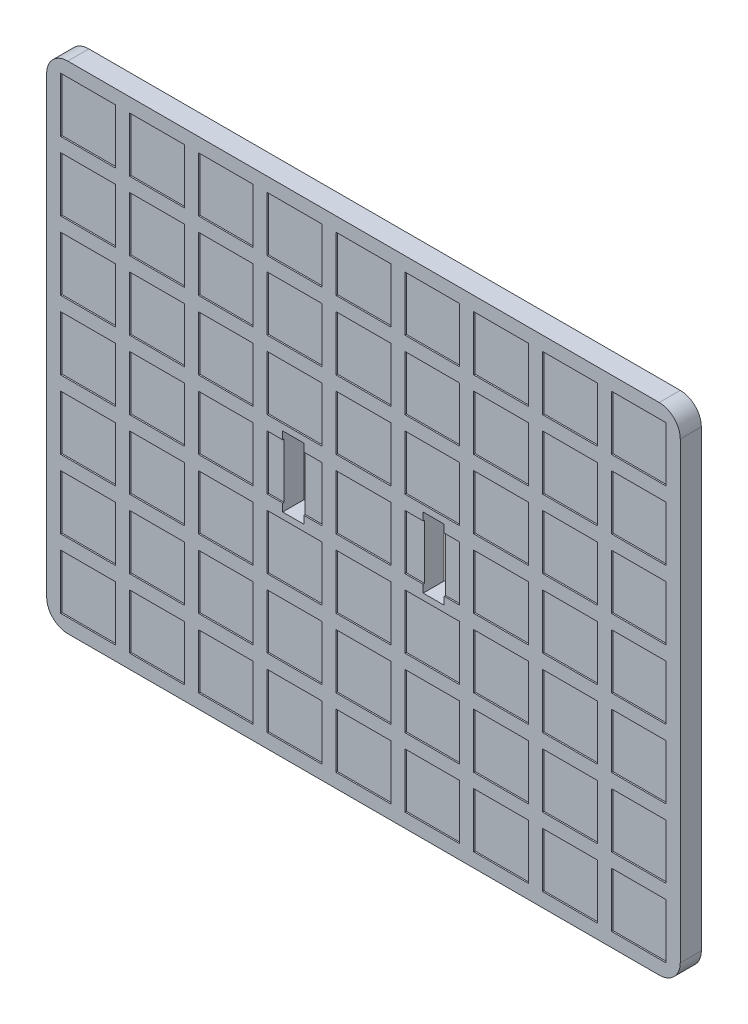
SolidWorks part; units mm, degrees
material "Maple"
ref_plane "Front Plane" through (0, 0, 0) normal (0, 0, 1) x (1, 0, 0)
ref_plane "Top Plane" through (0, 0, 0) normal (0, 1, 0) x (1, 0, 0)
ref_plane "Right Plane" through (0, 0, 0) normal (1, 0, 0) x (0, 0, -1)
sketch "Sketch1" plane through (0, 0, 0) normal (0, 0, 1) x (1, 0, 0)
  line L0 (-10, 0) -> (0, 0) construction
  line L1 (42.1, 35.3) -> (-42.1, 35.3)
  line L2 (45.1, 32.3) -> (45.1, -32.3)
  line L3 (42.1, -35.3) -> (-42.1, -35.3)
  line L4 (-45.1, 32.3) -> (-45.1, -32.3)
  line L5 (45.1, 35.3) -> (-45.1, -35.3) construction
  line L6 (45.1, -35.3) -> (-45.1, 35.3) construction
  line L7 (-11.5, 5) -> (-8.5, 5)
  line L8 (-11.5, 5) -> (-11.5, -5)
  line L9 (-11.5, -5) -> (-8.5, -5)
  line L10 (-8.5, 5) -> (-8.5, -5)
  line L11 (-11.5, 5) -> (-8.5, -5) construction
  line L12 (-11.5, -5) -> (-8.5, 5) construction
  line L13 (8.5, 5) -> (11.5, 5)
  line L14 (8.5, 5) -> (8.5, -5)
  line L15 (8.5, -5) -> (11.5, -5)
  line L16 (11.5, 5) -> (11.5, -5)
  line L17 (8.5, 5) -> (11.5, -5) construction
  line L18 (8.5, -5) -> (11.5, 5) construction
  line L19 (0, 0) -> (10, 0) construction
  arc A0 (-45.1, -32.3) -> (-42.1, -35.3) centre (-42.1, -32.3) ccw
  arc A1 (42.1, -35.3) -> (45.1, -32.3) centre (42.1, -32.3) ccw
  arc A2 (45.1, 32.3) -> (42.1, 35.3) centre (42.1, 32.3) ccw
  arc A3 (-42.1, 35.3) -> (-45.1, 32.3) centre (-42.1, 32.3) ccw
  point P0 (0, 0)
  point P5 (-10, 0)
  point P11 (10, 0)
  dimension "D6" = 3
  dimension "D1" = 20
  dimension "D2" = 3
  dimension "D3" = 10
  dimension "D4" = 90.2
  dimension "D5" = 70.6
extrude "Boss-Extrude1" add sketch "Sketch1" along normal blind 3
sketch "Sketch2" plane through (0, 0, 3) normal (0, 0, 1) x (1, 0, 0)
  line L1 (-43.1, 23.5) -> (-35.3, 23.5)
  line L2 (-43.1, 33.3) -> (-35.3, 33.3)
  line L3 (-43.1, 33.3) -> (-43.1, 25.5)
  line L4 (-43.1, 23.5) -> (-43.1, 15.7)
  line L5 (-43.1, 25.5) -> (-35.3, 25.5)
  line L6 (-35.3, 33.3) -> (-35.3, 25.5)
  line L7 (-33.3, 33.3) -> (-25.5, 33.3)
  line L8 (-33.3, 33.3) -> (-33.3, 25.5)
  line L9 (-33.3, 25.5) -> (-25.5, 25.5)
  line L10 (-25.5, 33.3) -> (-25.5, 25.5)
  line L11 (-35.3, 33.3) -> (-33.3, 33.3) construction
  line L12 (-23.5, 33.3) -> (-15.7, 33.3)
  line L13 (-23.5, 33.3) -> (-23.5, 25.5)
  line L14 (-23.5, 25.5) -> (-15.7, 25.5)
  line L15 (-15.7, 33.3) -> (-15.7, 25.5)
  line L16 (-13.7, 33.3) -> (-5.9, 33.3)
  line L17 (-13.7, 33.3) -> (-13.7, 25.5)
  line L18 (-13.7, 25.5) -> (-5.9, 25.5)
  line L19 (-5.9, 33.3) -> (-5.9, 25.5)
  line L20 (-3.9, 33.3) -> (3.9, 33.3)
  line L21 (-3.9, 33.3) -> (-3.9, 25.5)
  line L22 (-3.9, 25.5) -> (3.9, 25.5)
  line L23 (3.9, 33.3) -> (3.9, 25.5)
  line L24 (5.9, 33.3) -> (13.7, 33.3)
  line L25 (5.9, 33.3) -> (5.9, 25.5)
  line L26 (5.9, 25.5) -> (13.7, 25.5)
  line L27 (13.7, 33.3) -> (13.7, 25.5)
  line L28 (15.7, 33.3) -> (23.5, 33.3)
  line L29 (15.7, 33.3) -> (15.7, 25.5)
  line L30 (15.7, 25.5) -> (23.5, 25.5)
  line L31 (23.5, 33.3) -> (23.5, 25.5)
  line L32 (-43.1, 15.7) -> (-35.3, 15.7)
  line L33 (25.5, 33.3) -> (33.3, 33.3)
  line L34 (25.5, 33.3) -> (25.5, 25.5)
  line L35 (25.5, 25.5) -> (33.3, 25.5)
  line L36 (33.3, 33.3) -> (33.3, 25.5)
  line L37 (35.3, 33.3) -> (43.1, 33.3)
  line L38 (35.3, 33.3) -> (35.3, 25.5)
  line L39 (35.3, 25.5) -> (43.1, 25.5)
  line L40 (43.1, 33.3) -> (43.1, 25.5)
  line L41 (-23.5, 33.3) -> (-25.5, 33.3) construction
  line L42 (-13.7, 33.3) -> (-15.7, 33.3) construction
  line L43 (-3.9, 33.3) -> (-5.9, 33.3) construction
  line L44 (5.9, 33.3) -> (3.9, 33.3) construction
  line L45 (15.7, 33.3) -> (13.7, 33.3) construction
  line L46 (25.5, 33.3) -> (23.5, 33.3) construction
  line L47 (35.3, 33.3) -> (33.3, 33.3) construction
  line L48 (-35.3, 23.5) -> (-35.3, 15.7)
  line L49 (-33.3, 23.5) -> (-25.5, 23.5)
  line L50 (-33.3, 23.5) -> (-33.3, 15.7)
  line L51 (-33.3, 15.7) -> (-25.5, 15.7)
  line L52 (-25.5, 23.5) -> (-25.5, 15.7)
  line L53 (-35.3, 23.5) -> (-33.3, 23.5) construction
  line L54 (-23.5, 23.5) -> (-15.7, 23.5)
  line L55 (-23.5, 23.5) -> (-23.5, 15.7)
  line L56 (-23.5, 15.7) -> (-15.7, 15.7)
  line L57 (-15.7, 23.5) -> (-15.7, 15.7)
  line L58 (-13.7, 23.5) -> (-5.9, 23.5)
  line L59 (-13.7, 23.5) -> (-13.7, 15.7)
  line L60 (-13.7, 15.7) -> (-5.9, 15.7)
  line L61 (-5.9, 23.5) -> (-5.9, 15.7)
  line L62 (-3.9, 23.5) -> (3.9, 23.5)
  line L63 (-3.9, 23.5) -> (-3.9, 15.7)
  line L64 (-3.9, 15.7) -> (3.9, 15.7)
  line L65 (3.9, 23.5) -> (3.9, 15.7)
  line L66 (5.9, 23.5) -> (13.7, 23.5)
  line L67 (5.9, 23.5) -> (5.9, 15.7)
  line L68 (5.9, 15.7) -> (13.7, 15.7)
  line L69 (13.7, 23.5) -> (13.7, 15.7)
  line L70 (15.7, 23.5) -> (23.5, 23.5)
  line L71 (15.7, 23.5) -> (15.7, 15.7)
  line L72 (15.7, 15.7) -> (23.5, 15.7)
  line L73 (23.5, 23.5) -> (23.5, 15.7)
  line L74 (25.5, 23.5) -> (33.3, 23.5)
  line L75 (25.5, 23.5) -> (25.5, 15.7)
  line L76 (25.5, 15.7) -> (33.3, 15.7)
  line L77 (33.3, 23.5) -> (33.3, 15.7)
  line L78 (35.3, 23.5) -> (43.1, 23.5)
  line L79 (35.3, 23.5) -> (35.3, 15.7)
  line L80 (35.3, 15.7) -> (43.1, 15.7)
  line L81 (43.1, 23.5) -> (43.1, 15.7)
  line L82 (-23.5, 23.5) -> (-25.5, 23.5) construction
  line L83 (-13.7, 23.5) -> (-15.7, 23.5) construction
  line L84 (-3.9, 23.5) -> (-5.9, 23.5) construction
  line L85 (5.9, 23.5) -> (3.9, 23.5) construction
  line L86 (15.7, 23.5) -> (13.7, 23.5) construction
  line L87 (25.5, 23.5) -> (23.5, 23.5) construction
  line L88 (35.3, 23.5) -> (33.3, 23.5) construction
  line L90 (-43.1, 3.9) -> (-35.3, 3.9)
  line L91 (-43.1, 13.7) -> (-35.3, 13.7)
  line L92 (-43.1, 13.7) -> (-43.1, 5.9)
  line L93 (-43.1, 3.9) -> (-43.1, -3.9)
  line L94 (-43.1, 5.9) -> (-35.3, 5.9)
  line L95 (-35.3, 13.7) -> (-35.3, 5.9)
  line L96 (-33.3, 13.7) -> (-25.5, 13.7)
  line L97 (-33.3, 13.7) -> (-33.3, 5.9)
  line L98 (-33.3, 5.9) -> (-25.5, 5.9)
  line L99 (-25.5, 13.7) -> (-25.5, 5.9)
  line L100 (-35.3, 13.7) -> (-33.3, 13.7) construction
  line L101 (-23.5, 13.7) -> (-15.7, 13.7)
  line L102 (-23.5, 13.7) -> (-23.5, 5.9)
  line L103 (-23.5, 5.9) -> (-15.7, 5.9)
  line L104 (-15.7, 13.7) -> (-15.7, 5.9)
  line L105 (-13.7, 13.7) -> (-5.9, 13.7)
  line L106 (-13.7, 13.7) -> (-13.7, 5.9)
  line L107 (-13.7, 5.9) -> (-5.9, 5.9)
  line L108 (-5.9, 13.7) -> (-5.9, 5.9)
  line L109 (-3.9, 13.7) -> (3.9, 13.7)
  line L110 (-3.9, 13.7) -> (-3.9, 5.9)
  line L111 (-3.9, 5.9) -> (3.9, 5.9)
  line L112 (3.9, 13.7) -> (3.9, 5.9)
  line L113 (5.9, 13.7) -> (13.7, 13.7)
  line L114 (5.9, 13.7) -> (5.9, 5.9)
  line L115 (5.9, 5.9) -> (13.7, 5.9)
  line L116 (13.7, 13.7) -> (13.7, 5.9)
  line L117 (15.7, 13.7) -> (23.5, 13.7)
  line L118 (15.7, 13.7) -> (15.7, 5.9)
  line L119 (15.7, 5.9) -> (23.5, 5.9)
  line L120 (23.5, 13.7) -> (23.5, 5.9)
  line L121 (-43.1, -3.9) -> (-35.3, -3.9)
  line L122 (25.5, 13.7) -> (33.3, 13.7)
  line L123 (25.5, 13.7) -> (25.5, 5.9)
  line L124 (25.5, 5.9) -> (33.3, 5.9)
  line L125 (33.3, 13.7) -> (33.3, 5.9)
  line L126 (35.3, 13.7) -> (43.1, 13.7)
  line L127 (35.3, 13.7) -> (35.3, 5.9)
  line L128 (35.3, 5.9) -> (43.1, 5.9)
  line L129 (43.1, 13.7) -> (43.1, 5.9)
  line L130 (-23.5, 13.7) -> (-25.5, 13.7) construction
  line L131 (-13.7, 13.7) -> (-15.7, 13.7) construction
  line L132 (-3.9, 13.7) -> (-5.9, 13.7) construction
  line L133 (5.9, 13.7) -> (3.9, 13.7) construction
  line L134 (15.7, 13.7) -> (13.7, 13.7) construction
  line L135 (25.5, 13.7) -> (23.5, 13.7) construction
  line L136 (35.3, 13.7) -> (33.3, 13.7) construction
  line L137 (-35.3, 3.9) -> (-35.3, -3.9)
  line L138 (-33.3, 3.9) -> (-25.5, 3.9)
  line L139 (-33.3, 3.9) -> (-33.3, -3.9)
  line L140 (-33.3, -3.9) -> (-25.5, -3.9)
  line L141 (-25.5, 3.9) -> (-25.5, -3.9)
  line L142 (-35.3, 3.9) -> (-33.3, 3.9) construction
  line L143 (-23.5, 3.9) -> (-15.7, 3.9)
  line L144 (-23.5, 3.9) -> (-23.5, -3.9)
  line L145 (-23.5, -3.9) -> (-15.7, -3.9)
  line L146 (-15.7, 3.9) -> (-15.7, -3.9)
  line L147 (-13.7, 3.9) -> (-5.9, 3.9)
  line L148 (-13.7, 3.9) -> (-13.7, -3.9)
  line L149 (-13.7, -3.9) -> (-5.9, -3.9)
  line L150 (-5.9, 3.9) -> (-5.9, -3.9)
  line L151 (-3.9, 3.9) -> (3.9, 3.9)
  line L152 (-3.9, 3.9) -> (-3.9, -3.9)
  line L153 (-3.9, -3.9) -> (3.9, -3.9)
  line L154 (3.9, 3.9) -> (3.9, -3.9)
  line L155 (5.9, 3.9) -> (13.7, 3.9)
  line L156 (5.9, 3.9) -> (5.9, -3.9)
  line L157 (5.9, -3.9) -> (13.7, -3.9)
  line L158 (13.7, 3.9) -> (13.7, -3.9)
  line L159 (15.7, 3.9) -> (23.5, 3.9)
  line L160 (15.7, 3.9) -> (15.7, -3.9)
  line L161 (15.7, -3.9) -> (23.5, -3.9)
  line L162 (23.5, 3.9) -> (23.5, -3.9)
  line L163 (25.5, 3.9) -> (33.3, 3.9)
  line L164 (25.5, 3.9) -> (25.5, -3.9)
  line L165 (25.5, -3.9) -> (33.3, -3.9)
  line L166 (33.3, 3.9) -> (33.3, -3.9)
  line L167 (35.3, 3.9) -> (43.1, 3.9)
  line L168 (35.3, 3.9) -> (35.3, -3.9)
  line L169 (35.3, -3.9) -> (43.1, -3.9)
  line L170 (43.1, 3.9) -> (43.1, -3.9)
  line L171 (-23.5, 3.9) -> (-25.5, 3.9) construction
  line L172 (-13.7, 3.9) -> (-15.7, 3.9) construction
  line L173 (-3.9, 3.9) -> (-5.9, 3.9) construction
  line L174 (5.9, 3.9) -> (3.9, 3.9) construction
  line L175 (15.7, 3.9) -> (13.7, 3.9) construction
  line L176 (25.5, 3.9) -> (23.5, 3.9) construction
  line L177 (35.3, 3.9) -> (33.3, 3.9) construction
  line L178 (-43.1, -15.7) -> (-35.3, -15.7)
  line L179 (-43.1, -5.9) -> (-35.3, -5.9)
  line L180 (-43.1, -5.9) -> (-43.1, -13.7)
  line L181 (-43.1, -15.7) -> (-43.1, -23.5)
  line L182 (-43.1, -13.7) -> (-35.3, -13.7)
  line L183 (-35.3, -5.9) -> (-35.3, -13.7)
  line L184 (-33.3, -5.9) -> (-25.5, -5.9)
  line L185 (-33.3, -5.9) -> (-33.3, -13.7)
  line L186 (-33.3, -13.7) -> (-25.5, -13.7)
  line L187 (-25.5, -5.9) -> (-25.5, -13.7)
  line L188 (-35.3, -5.9) -> (-33.3, -5.9) construction
  line L189 (-23.5, -5.9) -> (-15.7, -5.9)
  line L190 (-23.5, -5.9) -> (-23.5, -13.7)
  line L191 (-23.5, -13.7) -> (-15.7, -13.7)
  line L192 (-15.7, -5.9) -> (-15.7, -13.7)
  line L193 (-13.7, -5.9) -> (-5.9, -5.9)
  line L194 (-13.7, -5.9) -> (-13.7, -13.7)
  line L195 (-13.7, -13.7) -> (-5.9, -13.7)
  line L196 (-5.9, -5.9) -> (-5.9, -13.7)
  line L197 (-3.9, -5.9) -> (3.9, -5.9)
  line L198 (-3.9, -5.9) -> (-3.9, -13.7)
  line L199 (-3.9, -13.7) -> (3.9, -13.7)
  line L200 (3.9, -5.9) -> (3.9, -13.7)
  line L201 (5.9, -5.9) -> (13.7, -5.9)
  line L202 (5.9, -5.9) -> (5.9, -13.7)
  line L203 (5.9, -13.7) -> (13.7, -13.7)
  line L204 (13.7, -5.9) -> (13.7, -13.7)
  line L205 (15.7, -5.9) -> (23.5, -5.9)
  line L206 (15.7, -5.9) -> (15.7, -13.7)
  line L207 (15.7, -13.7) -> (23.5, -13.7)
  line L208 (23.5, -5.9) -> (23.5, -13.7)
  line L209 (-43.1, -23.5) -> (-35.3, -23.5)
  line L210 (25.5, -5.9) -> (33.3, -5.9)
  line L211 (25.5, -5.9) -> (25.5, -13.7)
  line L212 (25.5, -13.7) -> (33.3, -13.7)
  line L213 (33.3, -5.9) -> (33.3, -13.7)
  line L214 (35.3, -5.9) -> (43.1, -5.9)
  line L215 (35.3, -5.9) -> (35.3, -13.7)
  line L216 (35.3, -13.7) -> (43.1, -13.7)
  line L217 (43.1, -5.9) -> (43.1, -13.7)
  line L218 (-23.5, -5.9) -> (-25.5, -5.9) construction
  line L219 (-13.7, -5.9) -> (-15.7, -5.9) construction
  line L220 (-3.9, -5.9) -> (-5.9, -5.9) construction
  line L221 (5.9, -5.9) -> (3.9, -5.9) construction
  line L222 (15.7, -5.9) -> (13.7, -5.9) construction
  line L223 (25.5, -5.9) -> (23.5, -5.9) construction
  line L224 (35.3, -5.9) -> (33.3, -5.9) construction
  line L225 (-35.3, -15.7) -> (-35.3, -23.5)
  line L226 (-33.3, -15.7) -> (-25.5, -15.7)
  line L227 (-33.3, -15.7) -> (-33.3, -23.5)
  line L228 (-33.3, -23.5) -> (-25.5, -23.5)
  line L229 (-25.5, -15.7) -> (-25.5, -23.5)
  line L230 (-35.3, -15.7) -> (-33.3, -15.7) construction
  line L231 (-23.5, -15.7) -> (-15.7, -15.7)
  line L232 (-23.5, -15.7) -> (-23.5, -23.5)
  line L233 (-23.5, -23.5) -> (-15.7, -23.5)
  line L234 (-15.7, -15.7) -> (-15.7, -23.5)
  line L235 (-13.7, -15.7) -> (-5.9, -15.7)
  line L236 (-13.7, -15.7) -> (-13.7, -23.5)
  line L237 (-13.7, -23.5) -> (-5.9, -23.5)
  line L238 (-5.9, -15.7) -> (-5.9, -23.5)
  line L239 (-3.9, -15.7) -> (3.9, -15.7)
  line L240 (-3.9, -15.7) -> (-3.9, -23.5)
  line L241 (-3.9, -23.5) -> (3.9, -23.5)
  line L242 (3.9, -15.7) -> (3.9, -23.5)
  line L243 (5.9, -15.7) -> (13.7, -15.7)
  line L244 (5.9, -15.7) -> (5.9, -23.5)
  line L245 (5.9, -23.5) -> (13.7, -23.5)
  line L246 (13.7, -15.7) -> (13.7, -23.5)
  line L247 (15.7, -15.7) -> (23.5, -15.7)
  line L248 (15.7, -15.7) -> (15.7, -23.5)
  line L249 (15.7, -23.5) -> (23.5, -23.5)
  line L250 (23.5, -15.7) -> (23.5, -23.5)
  line L251 (25.5, -15.7) -> (33.3, -15.7)
  line L252 (25.5, -15.7) -> (25.5, -23.5)
  line L253 (25.5, -23.5) -> (33.3, -23.5)
  line L254 (33.3, -15.7) -> (33.3, -23.5)
  line L255 (35.3, -15.7) -> (43.1, -15.7)
  line L256 (35.3, -15.7) -> (35.3, -23.5)
  line L257 (35.3, -23.5) -> (43.1, -23.5)
  line L258 (43.1, -15.7) -> (43.1, -23.5)
  line L259 (-23.5, -15.7) -> (-25.5, -15.7) construction
  line L260 (-13.7, -15.7) -> (-15.7, -15.7) construction
  line L261 (-3.9, -15.7) -> (-5.9, -15.7) construction
  line L262 (5.9, -15.7) -> (3.9, -15.7) construction
  line L263 (15.7, -15.7) -> (13.7, -15.7) construction
  line L264 (25.5, -15.7) -> (23.5, -15.7) construction
  line L265 (35.3, -15.7) -> (33.3, -15.7) construction
  line L266 (-43.1, -25.5) -> (-35.3, -25.5)
  line L267 (-43.1, -25.5) -> (-43.1, -33.3)
  line L268 (-43.1, -33.3) -> (-35.3, -33.3)
  line L269 (-35.3, -25.5) -> (-35.3, -33.3)
  line L270 (-33.3, -25.5) -> (-25.5, -25.5)
  line L271 (-33.3, -25.5) -> (-33.3, -33.3)
  line L272 (-33.3, -33.3) -> (-25.5, -33.3)
  line L273 (-25.5, -25.5) -> (-25.5, -33.3)
  line L274 (-35.3, -25.5) -> (-33.3, -25.5) construction
  line L275 (-23.5, -25.5) -> (-15.7, -25.5)
  line L276 (-23.5, -25.5) -> (-23.5, -33.3)
  line L277 (-23.5, -33.3) -> (-15.7, -33.3)
  line L278 (-15.7, -25.5) -> (-15.7, -33.3)
  line L279 (-13.7, -25.5) -> (-5.9, -25.5)
  line L280 (-13.7, -25.5) -> (-13.7, -33.3)
  line L281 (-13.7, -33.3) -> (-5.9, -33.3)
  line L282 (-5.9, -25.5) -> (-5.9, -33.3)
  line L283 (-3.9, -25.5) -> (3.9, -25.5)
  line L284 (-3.9, -25.5) -> (-3.9, -33.3)
  line L285 (-3.9, -33.3) -> (3.9, -33.3)
  line L286 (3.9, -25.5) -> (3.9, -33.3)
  line L287 (5.9, -25.5) -> (13.7, -25.5)
  line L288 (5.9, -25.5) -> (5.9, -33.3)
  line L289 (5.9, -33.3) -> (13.7, -33.3)
  line L290 (13.7, -25.5) -> (13.7, -33.3)
  line L291 (15.7, -25.5) -> (23.5, -25.5)
  line L292 (15.7, -25.5) -> (15.7, -33.3)
  line L293 (15.7, -33.3) -> (23.5, -33.3)
  line L294 (23.5, -25.5) -> (23.5, -33.3)
  line L295 (25.5, -25.5) -> (33.3, -25.5)
  line L296 (25.5, -25.5) -> (25.5, -33.3)
  line L297 (25.5, -33.3) -> (33.3, -33.3)
  line L298 (33.3, -25.5) -> (33.3, -33.3)
  line L299 (35.3, -25.5) -> (43.1, -25.5)
  line L300 (35.3, -25.5) -> (35.3, -33.3)
  line L301 (35.3, -33.3) -> (43.1, -33.3)
  line L302 (43.1, -25.5) -> (43.1, -33.3)
  line L303 (-23.5, -25.5) -> (-25.5, -25.5) construction
  line L304 (-13.7, -25.5) -> (-15.7, -25.5) construction
  line L305 (-3.9, -25.5) -> (-5.9, -25.5) construction
  line L306 (5.9, -25.5) -> (3.9, -25.5) construction
  line L307 (15.7, -25.5) -> (13.7, -25.5) construction
  line L308 (25.5, -25.5) -> (23.5, -25.5) construction
  line L309 (35.3, -25.5) -> (33.3, -25.5) construction
  line L311 (-45.1, 32.3) -> (-45.1, -32.3) construction
  line L312 (-42.1, -35.3) -> (42.1, -35.3) construction
  point P75 (0, 0)
  point P260 (0, 0)
  point P261 (0, 0)
  point P262 (0, 0)
  point P263 (0, 0)
  point P264 (0, 0)
  point P265 (0, 0)
  point P266 (0, 0)
  point P267 (0, 0)
  point P268 (0, 0)
  point P269 (0, 0)
  point P270 (0, 0)
  point P271 (0, 0)
  point P272 (0, 0)
  dimension "D1" = 7.8
  dimension "D2" = 2
  dimension "D3" = 2
  dimension "D4" = 2
  dimension "D5" = 2
  dimension "D6" = 2
  dimension "D7" = 2
  dimension "D8" = 2
  dimension "D9" = 2
  dimension "D10" = 2
  dimension "D11" = 2
  dimension "D13" = 2
  dimension "D14" = 2
  dimension "D15" = 2
  dimension "D16" = 2
  dimension "D17" = 2
extrude "Cut-Extrude1" cut sketch "Sketch2" against normal blind 0.2
